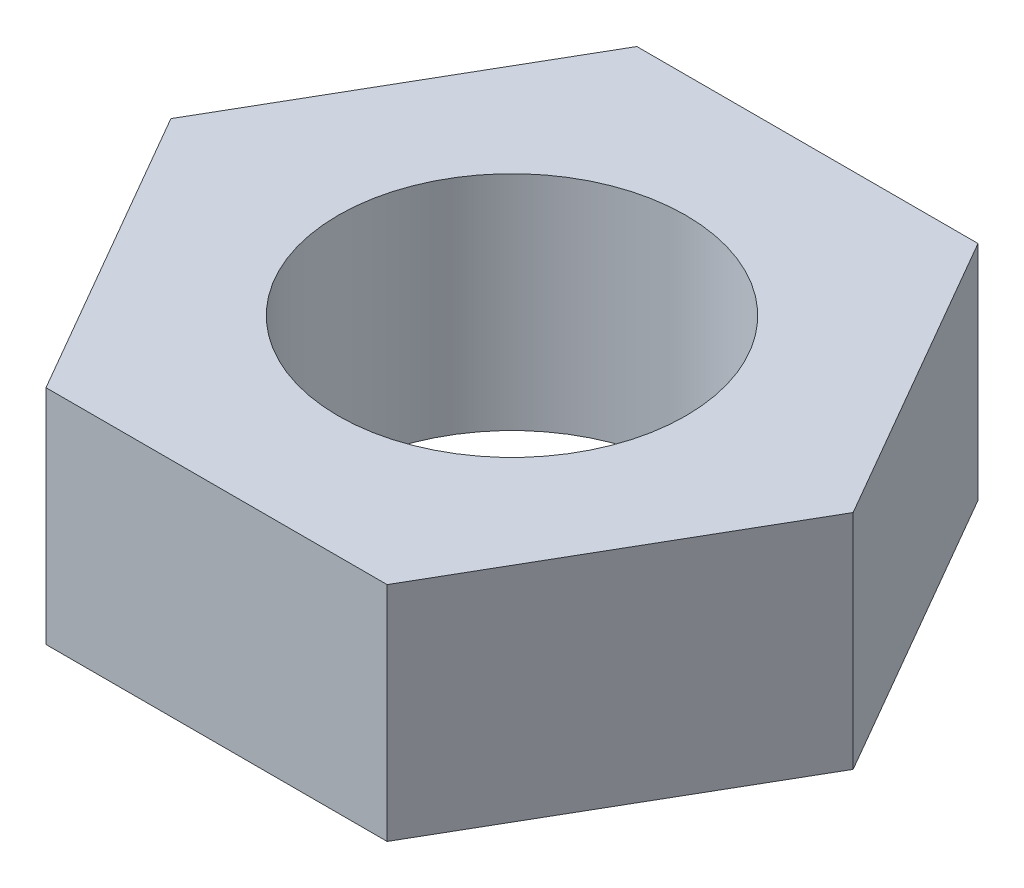
SolidWorks part; units mm, degrees
ref_plane "Front Plane" through (0, 0, 0) normal (0, 0, 1) x (1, 0, 0)
ref_plane "Top Plane" through (0, 0, 0) normal (0, 1, 0) x (1, 0, 0)
ref_plane "Right Plane" through (0, 0, 0) normal (1, 0, 0) x (0, 0, -1)
sketch "Sketch1" plane through (0, 0, 0) normal (0, 1, 0) x (1, 0, 0)
  line L1 (4.9075, 8.5) -> (-4.9075, 8.5)
  line L2 (-4.9075, 8.5) -> (-9.815, 0)
  line L3 (-9.815, 0) -> (-4.9075, -8.5)
  line L4 (-4.9075, -8.5) -> (4.9075, -8.5)
  line L5 (4.9075, -8.5) -> (9.815, 0)
  line L6 (9.815, 0) -> (4.9075, 8.5)
  circle A0 centre (0, 0) radius 8.5 construction
  circle A1 centre (0, 0) radius 5
  dimension "D2" = 10
  dimension "D1" = 17
extrude "Boss-Extrude1" add sketch "Sketch1" along normal mid plane 6.4
